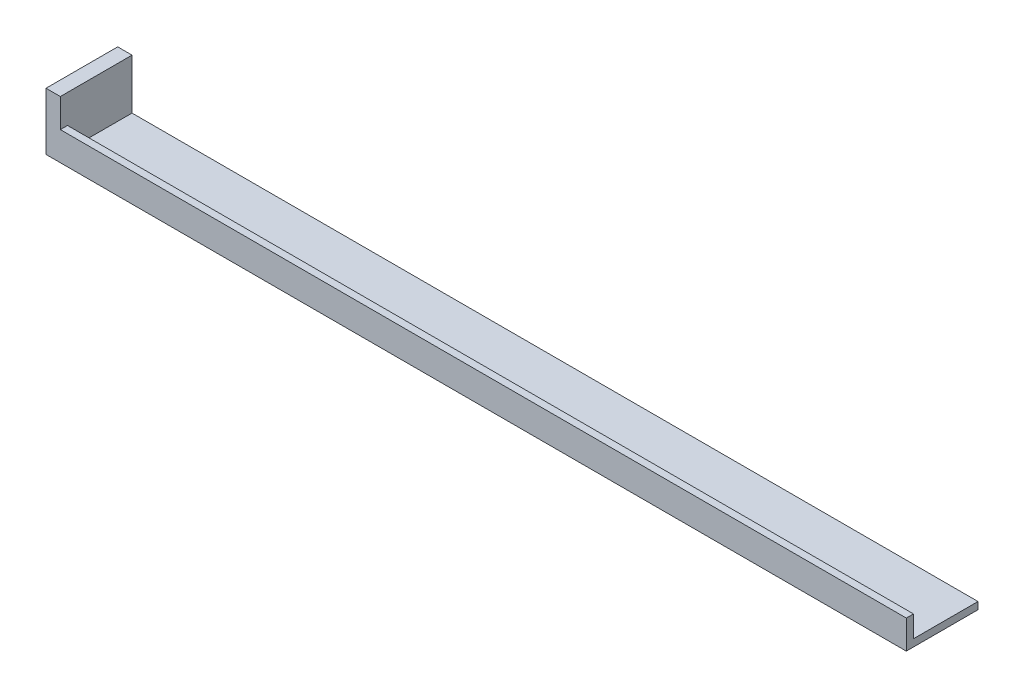
SolidWorks part; units mm, degrees
ref_plane "Ön Düzlem" through (0, 0, 0) normal (0, 0, 1) x (1, 0, 0)
ref_plane "Üst Düzlem" through (0, 0, 0) normal (0, 1, 0) x (1, 0, 0)
ref_plane "Sağ Düzlem" through (0, 0, 0) normal (1, 0, 0) x (0, 0, -1)
sketch "Çizim1" plane through (0, 0, 0) normal (0, 0, 1) x (1, 0, 0)
  line L0 (0, 0) -> (-120, 0)
  line L1 (0, 0) -> (0, 3)
  line L2 (0, 3) -> (2, 3)
  line L3 (2, 3) -> (2, -1)
  line L4 (2, -1) -> (-120, -1)
  line L5 (-120, 0) -> (-120, -1)
  dimension "D1" = 120
extrude "Yükseklik-Ekstrüzyon1" add sketch "Çizim1" along normal blind 10
sketch "Çizim2" plane through (0, 0, 0) normal (0, 1, 0) x (1, 0, 0)
  line L0 (0, -10) -> (0, 0) construction
  line L1 (-120, -10) -> (0, -10)
  line L2 (-120, -10) -> (-120, -9)
  line L3 (-120, -9) -> (0, -9)
  line L4 (0, -10) -> (0, -9)
  dimension "D1" = 1
extrude "Yükseklik-Ekstrüzyon2" add sketch "Çizim2" along normal up to surface (3 mm away) up to face at (1, 3, 5)
sketch "Çizim4" plane through (0, 3, 0) normal (0, 1, 0) x (1, 0, 0)
  line L1 (0, 0) -> (2, 0)
  line L2 (0, 0) -> (0, -10)
  line L3 (0, -10) -> (2, -10)
  line L4 (2, 0) -> (2, -10)
extrude "Yükseklik-Ekstrüzyon3" add sketch "Çizim4" along normal blind 4
mirror "Aynalama1" about plane through (0, 0, 10) normal (1, 0, 0) of "Yükseklik-Ekstrüzyon3", "Yükseklik-Ekstrüzyon2", "Yükseklik-Ekstrüzyon1"
sketch "Çizim5" plane through (0, 0, 0) normal (0, 0, -1) x (-1, 0, 0)
  line L0 (0, 7) -> (0, -4.163)
  line L1 (-2, 7) -> (2, 7) construction
  line L2 (0, -4.163) -> (124.6468, -4.163)
  line L3 (124.6468, -4.163) -> (124.6468, 13.3505)
  line L4 (124.6468, 13.3505) -> (0, 13.3505)
  line L5 (0, 13.3505) -> (0, 7)
extrude "Kes-Ekstrüzyon1" cut sketch "Çizim5" against normal blind 33
